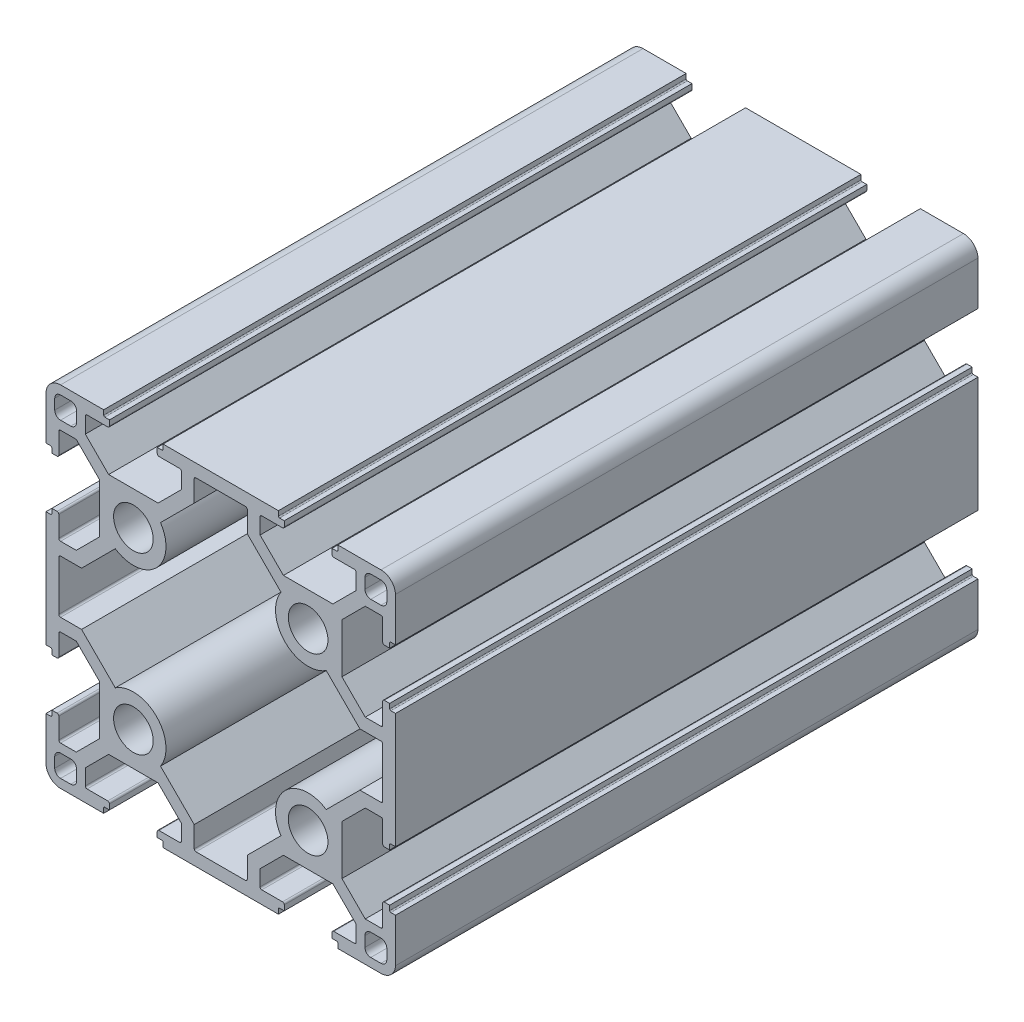
SolidWorks part; units mm, degrees
ref_plane "前视基准面" through (0, 0, 0) normal (0, 0, 1) x (1, 0, 0)
ref_plane "上视基准面" through (0, 0, 0) normal (0, 1, 0) x (1, 0, 0)
ref_plane "右视基准面" through (0, 0, 0) normal (1, 0, 0) x (0, 0, -1)
sketch "草图1" plane through (0, 0, 0) normal (0, 0, 1) x (1, 0, 0)
  line L0 (26.5416, -24.1862) -> (28.2916, -24.1862)
  line L1 (29.2916, -25.1862) -> (29.2916, -26.9362)
  line L2 (28.2916, -27.9362) -> (26.5416, -27.9362)
  line L3 (25.5416, -26.9362) -> (25.5416, -25.1862)
  line L4 (-23.963, -25.1862) -> (-23.963, -26.9362)
  line L5 (-24.963, -27.9362) -> (-26.713, -27.9362)
  line L6 (-27.713, -26.9362) -> (-27.713, -25.1862)
  line L7 (-26.713, -24.1862) -> (-24.963, -24.1862)
  line L8 (25.5416, 26.3138) -> (25.5416, 28.0638)
  line L9 (26.5416, 29.0638) -> (28.2916, 29.0638)
  line L10 (29.2916, 28.0638) -> (29.2916, 26.3138)
  line L11 (28.2916, 25.3138) -> (26.5416, 25.3138)
  line L12 (-24.963, 25.3138) -> (-26.713, 25.3138)
  line L13 (-27.713, 26.3138) -> (-27.713, 28.0638)
  line L14 (-26.713, 29.0638) -> (-24.963, 29.0638)
  line L15 (-23.963, 28.0638) -> (-23.963, 26.3138)
  line L16 (-9.5511, 18.67) -> (-3.763, 24.4581)
  line L17 (-3.763, 24.4581) -> (-3.763, 28.0638)
  line L18 (-3.463, 28.3638) -> (0.7893, 28.3638)
  line L19 (0.7893, 28.3638) -> (5.0416, 28.3638)
  line L20 (5.3416, 28.0638) -> (5.3416, 24.4581)
  line L21 (5.3416, 24.4581) -> (11.1297, 18.67)
  line L22 (18.8955, 10.9042) -> (24.6837, 5.1161)
  line L23 (24.6837, 5.1161) -> (28.2893, 5.1161)
  line L24 (28.5893, 4.8161) -> (28.5893, 0.5638)
  line L25 (28.5893, 0.5638) -> (28.5893, -3.6885)
  line L26 (28.2893, -3.9885) -> (24.6837, -3.9885)
  line L27 (24.6837, -3.9885) -> (18.8955, -9.7767)
  line L28 (11.1297, -17.5424) -> (5.3416, -23.3306)
  line L29 (5.3416, -23.3306) -> (5.3416, -26.9362)
  line L30 (5.0416, -27.2362) -> (0.7893, -27.2362)
  line L31 (0.7893, -27.2362) -> (-3.463, -27.2362)
  line L32 (-3.763, -26.9362) -> (-3.763, -23.3306)
  line L33 (-3.763, -23.3306) -> (-9.5511, -17.5424)
  line L34 (-17.3169, -9.7767) -> (-23.1051, -3.9885)
  line L35 (-23.1051, -3.9885) -> (-26.7107, -3.9885)
  line L36 (-27.0107, -3.6885) -> (-27.0107, 4.8161)
  line L37 (-26.7107, 5.1161) -> (-23.1051, 5.1161)
  line L38 (-23.1051, 5.1161) -> (-17.3169, 10.9042)
  line L39 (21.5916, 19.8081) -> (25.5972, 23.8138)
  line L40 (25.5972, 23.8138) -> (28.2916, 23.8138)
  line L41 (28.5916, 23.5138) -> (28.5916, 19.9638)
  line L42 (28.8916, 19.6638) -> (29.7916, 19.6638)
  line L43 (29.7916, 19.6638) -> (29.7916, 20.4638)
  line L44 (29.9916, 20.6638) -> (30.7893, 20.6638)
  line L45 (30.7893, 20.6638) -> (30.7893, 28.1702)
  line L46 (28.2916, 30.5638) -> (20.8916, 30.5638)
  line L47 (20.8916, 30.5638) -> (20.8916, 29.7638)
  line L48 (20.6916, 29.5638) -> (19.8916, 29.5638)
  line L49 (19.8916, 29.5638) -> (19.8916, 28.6638)
  line L50 (20.1916, 28.3638) -> (23.7416, 28.3638)
  line L51 (24.0416, 28.0638) -> (24.0416, 25.3694)
  line L52 (24.0416, 25.3694) -> (20.0359, 21.3638)
  line L53 (20.0359, 21.3638) -> (11.5472, 21.3638)
  line L54 (11.5472, 21.3638) -> (7.5416, 25.3694)
  line L55 (7.5416, 25.3694) -> (7.5416, 28.0638)
  line L56 (7.8416, 28.3638) -> (11.3916, 28.3638)
  line L57 (11.6916, 28.6638) -> (11.6916, 29.5638)
  line L58 (11.6916, 29.5638) -> (10.8916, 29.5638)
  line L59 (10.6916, 29.7638) -> (10.6916, 30.5638)
  line L60 (10.6916, 30.5638) -> (3.2916, 30.5638)
  line L61 (3.2916, 30.5638) -> (0.7893, 30.5638)
  line L62 (0.7893, 30.5638) -> (-9.113, 30.5638)
  line L63 (-9.113, 30.5638) -> (-9.113, 29.7638)
  line L64 (-9.313, 29.5638) -> (-10.113, 29.5638)
  line L65 (-10.113, 29.5638) -> (-10.113, 28.6638)
  line L66 (-9.813, 28.3638) -> (-6.263, 28.3638)
  line L67 (-5.963, 28.0638) -> (-5.963, 25.3694)
  line L68 (-5.963, 25.3694) -> (-9.9686, 21.3638)
  line L69 (-9.9686, 21.3638) -> (-18.4573, 21.3638)
  line L70 (-18.4573, 21.3638) -> (-22.463, 25.3694)
  line L71 (-22.463, 25.3694) -> (-22.463, 28.0638)
  line L72 (-22.163, 28.3638) -> (-18.613, 28.3638)
  line L73 (-18.313, 28.6638) -> (-18.313, 29.5638)
  line L74 (-18.313, 29.5638) -> (-19.113, 29.5638)
  line L75 (-19.313, 29.7638) -> (-19.313, 30.5638)
  line L76 (-19.313, 30.5638) -> (-26.713, 30.5638)
  line L77 (-29.2107, 28.1702) -> (-29.2107, 20.6638)
  line L78 (-29.2107, 20.6638) -> (-28.413, 20.6638)
  line L79 (-28.213, 20.4638) -> (-28.213, 19.6638)
  line L80 (-28.213, 19.6638) -> (-27.313, 19.6638)
  line L81 (-27.013, 19.9638) -> (-27.013, 23.5138)
  line L82 (-26.713, 23.8138) -> (-24.0186, 23.8138)
  line L83 (-24.0186, 23.8138) -> (-20.013, 19.8081)
  line L84 (-20.013, 19.8081) -> (-20.013, 11.3194)
  line L85 (-20.013, 11.3194) -> (-24.0186, 7.3138)
  line L86 (-24.0186, 7.3138) -> (-26.713, 7.3138)
  line L87 (-27.013, 7.6138) -> (-27.013, 11.1638)
  line L88 (-27.313, 11.4638) -> (-28.213, 11.4638)
  line L89 (-28.213, 11.4638) -> (-28.213, 10.6638)
  line L90 (-28.413, 10.4638) -> (-29.2107, 10.4638)
  line L91 (-29.2107, 10.4638) -> (-29.2107, -9.3362)
  line L92 (-29.2107, -9.3362) -> (-28.413, -9.3362)
  line L93 (-28.213, -9.5362) -> (-28.213, -10.3362)
  line L94 (-28.213, -10.3362) -> (-27.313, -10.3362)
  line L95 (-27.013, -10.0362) -> (-27.013, -6.4862)
  line L96 (-26.713, -6.1862) -> (-24.0186, -6.1862)
  line L97 (-24.0186, -6.1862) -> (-20.013, -10.1919)
  line L98 (-20.013, -10.1919) -> (-20.013, -18.6806)
  line L99 (-20.013, -18.6806) -> (-24.0186, -22.6862)
  line L100 (-24.0186, -22.6862) -> (-26.713, -22.6862)
  line L101 (-27.013, -22.3862) -> (-27.013, -18.8362)
  line L102 (-27.313, -18.5362) -> (-28.213, -18.5362)
  line L103 (-28.213, -18.5362) -> (-28.213, -19.3362)
  line L104 (-28.413, -19.5362) -> (-29.2107, -19.5362)
  line L105 (-29.2107, -19.5362) -> (-29.2107, -27.0426)
  line L106 (-26.713, -29.4362) -> (-19.313, -29.4362)
  line L107 (-19.313, -29.4362) -> (-19.313, -28.6362)
  line L108 (-19.113, -28.4362) -> (-18.313, -28.4362)
  line L109 (-18.313, -28.4362) -> (-18.313, -27.5362)
  line L110 (-18.613, -27.2362) -> (-22.163, -27.2362)
  line L111 (-22.463, -26.9362) -> (-22.463, -24.2419)
  line L112 (-22.463, -24.2419) -> (-18.4573, -20.2362)
  line L113 (-18.4573, -20.2362) -> (-9.9686, -20.2362)
  line L114 (-9.9686, -20.2362) -> (-5.963, -24.2419)
  line L115 (-5.963, -24.2419) -> (-5.963, -26.9362)
  line L116 (-6.263, -27.2362) -> (-9.813, -27.2362)
  line L117 (-10.113, -27.5362) -> (-10.113, -28.4362)
  line L118 (-10.113, -28.4362) -> (-9.313, -28.4362)
  line L119 (-9.113, -28.6362) -> (-9.113, -29.4362)
  line L120 (-9.113, -29.4362) -> (-1.713, -29.4362)
  line L121 (-1.713, -29.4362) -> (0.7893, -29.4362)
  line L122 (0.7893, -29.4362) -> (10.6916, -29.4362)
  line L123 (10.6916, -29.4362) -> (10.6916, -28.6362)
  line L124 (10.8916, -28.4362) -> (11.6916, -28.4362)
  line L125 (11.6916, -28.4362) -> (11.6916, -27.5362)
  line L126 (11.3916, -27.2362) -> (7.8416, -27.2362)
  line L127 (7.5416, -26.9362) -> (7.5416, -24.2419)
  line L128 (7.5416, -24.2419) -> (11.5472, -20.2362)
  line L129 (11.5472, -20.2362) -> (20.0359, -20.2362)
  line L130 (20.0359, -20.2362) -> (24.0416, -24.2419)
  line L131 (24.0416, -24.2419) -> (24.0416, -26.9362)
  line L132 (23.7416, -27.2362) -> (20.1916, -27.2362)
  line L133 (19.8916, -27.5362) -> (19.8916, -28.4362)
  line L134 (19.8916, -28.4362) -> (20.6916, -28.4362)
  line L135 (20.8916, -28.6362) -> (20.8916, -29.4362)
  line L136 (20.8916, -29.4362) -> (28.2916, -29.4362)
  line L137 (30.7893, -27.0426) -> (30.7893, -19.5362)
  line L138 (30.7893, -19.5362) -> (29.9916, -19.5362)
  line L139 (29.7916, -19.3362) -> (29.7916, -18.5362)
  line L140 (29.7916, -18.5362) -> (28.8916, -18.5362)
  line L141 (28.5916, -18.8362) -> (28.5916, -22.3862)
  line L142 (28.2916, -22.6862) -> (25.5972, -22.6862)
  line L143 (25.5972, -22.6862) -> (21.5916, -18.6806)
  line L144 (21.5916, -18.6806) -> (21.5916, -10.1919)
  line L145 (21.5916, -10.1919) -> (25.5972, -6.1862)
  line L146 (25.5972, -6.1862) -> (28.2916, -6.1862)
  line L147 (28.5916, -6.4862) -> (28.5916, -10.0362)
  line L148 (28.8916, -10.3362) -> (29.7916, -10.3362)
  line L149 (29.7916, -10.3362) -> (29.7916, -9.5362)
  line L150 (29.9916, -9.3362) -> (30.7893, -9.3362)
  line L151 (30.7893, -9.3362) -> (30.7893, 0.5638)
  line L152 (30.7893, 0.5638) -> (30.7893, 10.4638)
  line L153 (30.7893, 10.4638) -> (29.9916, 10.4638)
  line L154 (29.7916, 10.6638) -> (29.7916, 11.4638)
  line L155 (29.7916, 11.4638) -> (28.8916, 11.4638)
  line L156 (28.5916, 11.1638) -> (28.5916, 7.6138)
  line L157 (28.2916, 7.3138) -> (25.5972, 7.3138)
  line L158 (25.5972, 7.3138) -> (21.5916, 11.3194)
  line L159 (21.5916, 11.3194) -> (21.5916, 19.8081)
  arc A0 (29.2916, -25.1862) -> (28.2916, -24.1862) centre (28.2916, -25.1862) ccw
  arc A1 (28.2916, -27.9362) -> (29.2916, -26.9362) centre (28.2916, -26.9362) ccw
  arc A2 (25.5416, -26.9362) -> (26.5416, -27.9362) centre (26.5416, -26.9362) ccw
  arc A3 (26.5416, -24.1862) -> (25.5416, -25.1862) centre (26.5416, -25.1862) ccw
  arc A4 (-24.963, -27.9362) -> (-23.963, -26.9362) centre (-24.963, -26.9362) ccw
  arc A5 (-27.713, -26.9362) -> (-26.713, -27.9362) centre (-26.713, -26.9362) ccw
  arc A6 (-26.713, -24.1862) -> (-27.713, -25.1862) centre (-26.713, -25.1862) ccw
  arc A7 (-23.963, -25.1862) -> (-24.963, -24.1862) centre (-24.963, -25.1862) ccw
  circle A8 centre (15.7893, -14.4362) radius 3.4
  arc A9 (26.5416, 29.0638) -> (25.5416, 28.0638) centre (26.5416, 28.0638) ccw
  arc A10 (29.2916, 28.0638) -> (28.2916, 29.0638) centre (28.2916, 28.0638) ccw
  arc A11 (28.2916, 25.3138) -> (29.2916, 26.3138) centre (28.2916, 26.3138) ccw
  arc A12 (25.5416, 26.3138) -> (26.5416, 25.3138) centre (26.5416, 26.3138) ccw
  circle A13 centre (-14.2107, -14.4362) radius 3.4
  circle A14 centre (15.7893, 15.5638) radius 3.4
  arc A15 (-27.713, 26.3138) -> (-26.713, 25.3138) centre (-26.713, 26.3138) ccw
  arc A16 (-26.713, 29.0638) -> (-27.713, 28.0638) centre (-26.713, 28.0638) ccw
  arc A17 (-23.963, 28.0638) -> (-24.963, 29.0638) centre (-24.963, 28.0638) ccw
  arc A18 (-24.963, 25.3138) -> (-23.963, 26.3138) centre (-24.963, 26.3138) ccw
  arc A19 (-3.463, 28.3638) -> (-3.763, 28.0638) centre (-3.463, 28.0638) ccw
  arc A20 (5.3416, 28.0638) -> (5.0416, 28.3638) centre (5.0416, 28.0638) ccw
  arc A21 (11.1297, 18.67) -> (18.8955, 10.9042) centre (15.7893, 15.5638) ccw
  arc A22 (28.5893, 4.8161) -> (28.2893, 5.1161) centre (28.2893, 4.8161) ccw
  arc A23 (28.2893, -3.9885) -> (28.5893, -3.6885) centre (28.2893, -3.6885) ccw
  arc A24 (18.8955, -9.7767) -> (11.1297, -17.5424) centre (15.7893, -14.4362) ccw
  arc A25 (5.0416, -27.2362) -> (5.3416, -26.9362) centre (5.0416, -26.9362) ccw
  arc A26 (-3.763, -26.9362) -> (-3.463, -27.2362) centre (-3.463, -26.9362) ccw
  arc A27 (-9.5511, -17.5424) -> (-17.3169, -9.7767) centre (-14.2107, -14.4362) ccw
  arc A28 (-27.0107, -3.6885) -> (-26.7107, -3.9885) centre (-26.7107, -3.6885) ccw
  arc A29 (-26.7107, 5.1161) -> (-27.0107, 4.8161) centre (-26.7107, 4.8161) ccw
  arc A30 (-17.3169, 10.9042) -> (-9.5511, 18.67) centre (-14.2107, 15.5638) ccw
  circle A31 centre (-14.2107, 15.5638) radius 3.4
  arc A32 (28.5916, 23.5138) -> (28.2916, 23.8138) centre (28.2916, 23.5138) ccw
  arc A33 (28.5916, 19.9638) -> (28.8916, 19.6638) centre (28.8916, 19.9638) ccw
  arc A34 (29.9916, 20.6638) -> (29.7916, 20.4638) centre (29.9916, 20.4638) ccw
  arc A35 (30.7893, 28.1702) -> (28.2916, 30.5638) centre (28.2916, 28.0638) ccw
  arc A36 (20.6916, 29.5638) -> (20.8916, 29.7638) centre (20.6916, 29.7638) ccw
  arc A37 (19.8916, 28.6638) -> (20.1916, 28.3638) centre (20.1916, 28.6638) ccw
  arc A38 (24.0416, 28.0638) -> (23.7416, 28.3638) centre (23.7416, 28.0638) ccw
  arc A39 (7.8416, 28.3638) -> (7.5416, 28.0638) centre (7.8416, 28.0638) ccw
  arc A40 (11.3916, 28.3638) -> (11.6916, 28.6638) centre (11.3916, 28.6638) ccw
  arc A41 (10.6916, 29.7638) -> (10.8916, 29.5638) centre (10.8916, 29.7638) ccw
  arc A42 (-9.313, 29.5638) -> (-9.113, 29.7638) centre (-9.313, 29.7638) ccw
  arc A43 (-10.113, 28.6638) -> (-9.813, 28.3638) centre (-9.813, 28.6638) ccw
  arc A44 (-5.963, 28.0638) -> (-6.263, 28.3638) centre (-6.263, 28.0638) ccw
  arc A45 (-22.163, 28.3638) -> (-22.463, 28.0638) centre (-22.163, 28.0638) ccw
  arc A46 (-18.613, 28.3638) -> (-18.313, 28.6638) centre (-18.613, 28.6638) ccw
  arc A47 (-19.313, 29.7638) -> (-19.113, 29.5638) centre (-19.113, 29.7638) ccw
  arc A48 (-26.713, 30.5638) -> (-29.2107, 28.1702) centre (-26.713, 28.0638) ccw
  arc A49 (-28.213, 20.4638) -> (-28.413, 20.6638) centre (-28.413, 20.4638) ccw
  arc A50 (-27.313, 19.6638) -> (-27.013, 19.9638) centre (-27.313, 19.9638) ccw
  arc A51 (-26.713, 23.8138) -> (-27.013, 23.5138) centre (-26.713, 23.5138) ccw
  arc A52 (-27.013, 7.6138) -> (-26.713, 7.3138) centre (-26.713, 7.6138) ccw
  arc A53 (-27.013, 11.1638) -> (-27.313, 11.4638) centre (-27.313, 11.1638) ccw
  arc A54 (-28.413, 10.4638) -> (-28.213, 10.6638) centre (-28.413, 10.6638) ccw
  arc A55 (-28.213, -9.5362) -> (-28.413, -9.3362) centre (-28.413, -9.5362) ccw
  arc A56 (-27.313, -10.3362) -> (-27.013, -10.0362) centre (-27.313, -10.0362) ccw
  arc A57 (-26.713, -6.1862) -> (-27.013, -6.4862) centre (-26.713, -6.4862) ccw
  arc A58 (-27.013, -22.3862) -> (-26.713, -22.6862) centre (-26.713, -22.3862) ccw
  arc A59 (-27.013, -18.8362) -> (-27.313, -18.5362) centre (-27.313, -18.8362) ccw
  arc A60 (-28.413, -19.5362) -> (-28.213, -19.3362) centre (-28.413, -19.3362) ccw
  arc A61 (-29.2107, -27.0426) -> (-26.713, -29.4362) centre (-26.713, -26.9362) ccw
  arc A62 (-19.113, -28.4362) -> (-19.313, -28.6362) centre (-19.113, -28.6362) ccw
  arc A63 (-18.313, -27.5362) -> (-18.613, -27.2362) centre (-18.613, -27.5362) ccw
  arc A64 (-22.463, -26.9362) -> (-22.163, -27.2362) centre (-22.163, -26.9362) ccw
  arc A65 (-6.263, -27.2362) -> (-5.963, -26.9362) centre (-6.263, -26.9362) ccw
  arc A66 (-9.813, -27.2362) -> (-10.113, -27.5362) centre (-9.813, -27.5362) ccw
  arc A67 (-9.113, -28.6362) -> (-9.313, -28.4362) centre (-9.313, -28.6362) ccw
  arc A68 (10.8916, -28.4362) -> (10.6916, -28.6362) centre (10.8916, -28.6362) ccw
  arc A69 (11.6916, -27.5362) -> (11.3916, -27.2362) centre (11.3916, -27.5362) ccw
  arc A70 (7.5416, -26.9362) -> (7.8416, -27.2362) centre (7.8416, -26.9362) ccw
  arc A71 (23.7416, -27.2362) -> (24.0416, -26.9362) centre (23.7416, -26.9362) ccw
  arc A72 (20.1916, -27.2362) -> (19.8916, -27.5362) centre (20.1916, -27.5362) ccw
  arc A73 (20.8916, -28.6362) -> (20.6916, -28.4362) centre (20.6916, -28.6362) ccw
  arc A74 (28.2916, -29.4362) -> (30.7893, -27.0426) centre (28.2916, -26.9362) ccw
  arc A75 (29.7916, -19.3362) -> (29.9916, -19.5362) centre (29.9916, -19.3362) ccw
  arc A76 (28.8916, -18.5362) -> (28.5916, -18.8362) centre (28.8916, -18.8362) ccw
  arc A77 (28.2916, -22.6862) -> (28.5916, -22.3862) centre (28.2916, -22.3862) ccw
  arc A78 (28.5916, -6.4862) -> (28.2916, -6.1862) centre (28.2916, -6.4862) ccw
  arc A79 (28.5916, -10.0362) -> (28.8916, -10.3362) centre (28.8916, -10.0362) ccw
  arc A80 (29.9916, -9.3362) -> (29.7916, -9.5362) centre (29.9916, -9.5362) ccw
  arc A81 (29.7916, 10.6638) -> (29.9916, 10.4638) centre (29.9916, 10.6638) ccw
  arc A82 (28.8916, 11.4638) -> (28.5916, 11.1638) centre (28.8916, 11.1638) ccw
  arc A83 (28.2916, 7.3138) -> (28.5916, 7.6138) centre (28.2916, 7.6138) ccw
extrude "凸台-拉伸1" add sketch "草图1" along normal blind 100
